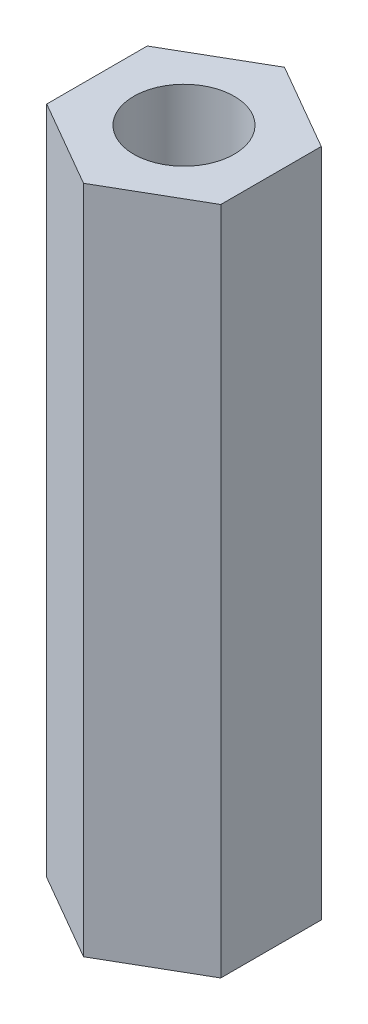
SolidWorks part; units mm, degrees
ref_plane "Front Plane" through (0, 0, 0) normal (0, 0, 1) x (1, 0, 0)
ref_plane "Top Plane" through (0, 0, 0) normal (0, 1, 0) x (1, 0, 0)
ref_plane "Right Plane" through (0, 0, 0) normal (1, 0, 0) x (0, 0, -1)
sketch "Sketch1" plane through (0, 0, 0) normal (0, 1, 0) x (1, 0, 0)
  line L0 (0, -3) -> (0, 3) construction
  line L1 (-2.5981, -1.5) -> (2.5981, 1.5) construction
  line L2 (2.5981, -1.5) -> (-2.5981, 1.5) construction
  line L3 (0, 3) -> (-2.5981, 1.5)
  line L4 (-2.5981, 1.5) -> (-2.5981, -1.5)
  line L5 (-2.5981, -1.5) -> (0, -3)
  line L6 (0, -3) -> (2.5981, -1.5)
  line L7 (2.5981, -1.5) -> (2.5981, 1.5)
  line L8 (2.5981, 1.5) -> (0, 3)
  circle A0 centre (0, 0) radius 1.5
  circle A1 centre (0, 0) radius 3 construction
  point P7 (0, 0)
  point P10 (0, 0)
  point P13 (0, 0)
extrude "Boss-Extrude1" add sketch "Sketch1" along normal blind 20
